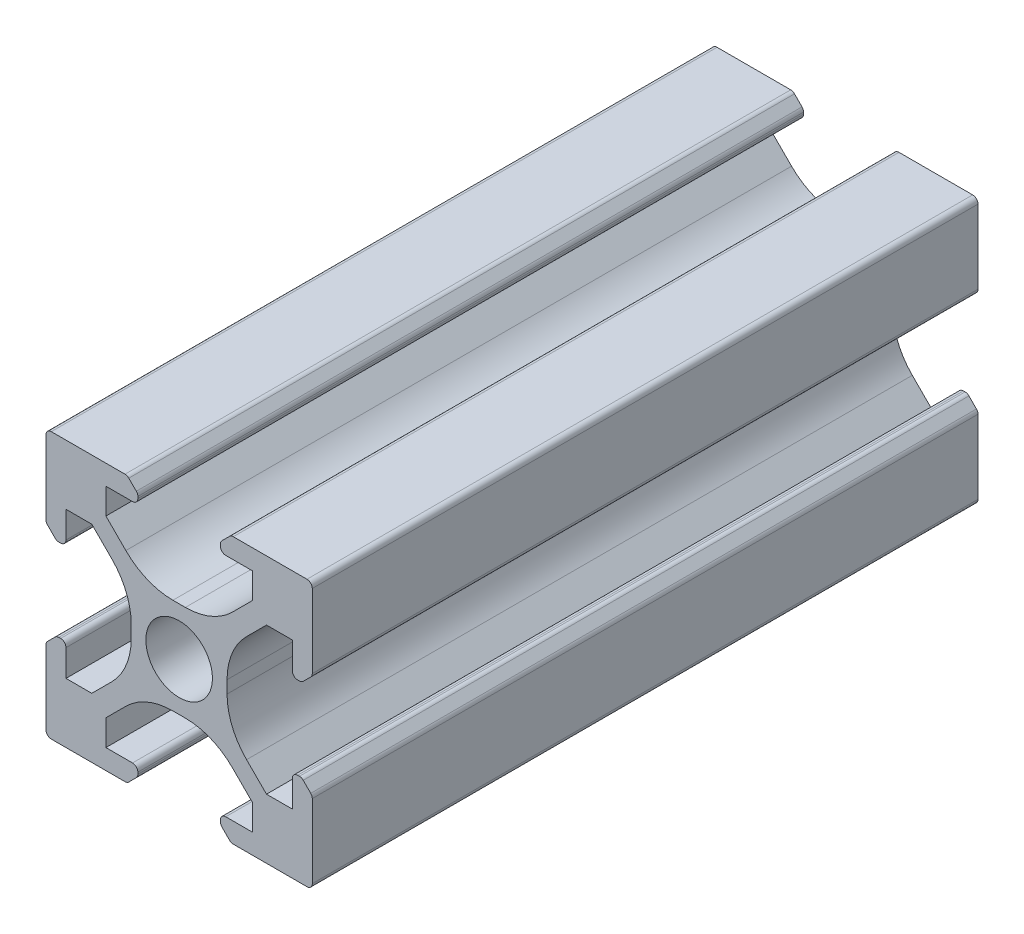
SolidWorks part; units mm, degrees
material "6063-T83"
ref_plane "Plano frontal" through (0, 0, 0) normal (0, 0, 1) x (1, 0, 0)
ref_plane "Plano superior" through (0, 0, 0) normal (0, 1, 0) x (1, 0, 0)
ref_plane "Plano direito" through (0, 0, 0) normal (1, 0, 0) x (0, 0, -1)
sketch "Esboço1" plane through (0, 0, 0) normal (0, 0, 1) x (1, 0, 0)
  line L0 (-9.0343, 3.1) -> (-8.9, 3.1)
  line L3 (-10, 10) -> (-4.0657, 10)
  line L5 (-10, -10) -> (10, 10) construction
  line L6 (-10, 10) -> (10, -10) construction
  line L7 (-8.5, 3.5) -> (-8.5, 5.5)
  line L8 (-10, 0) -> (10, 0) construction
  line L9 (0, 10) -> (0, -10) construction
  line L12 (-8.5, 5.5) -> (-6.5607, 5.5)
  line L15 (-6.5607, 5.5) -> (-5.0645, 4.0038)
  line L16 (-3.6, 0.4683) -> (-3.6, 0)
  line L17 (-0.4683, 3.6) -> (0, 3.6)
  line L18 (-5.5, 6.5607) -> (-4.0038, 5.0645)
  line L21 (-5.5, 8.5) -> (-5.5, 6.5607)
  line L24 (-3.5, 8.5) -> (-5.5, 8.5)
  line L25 (-3.1, 9.0343) -> (-3.1, 8.9)
  line L44 (-10, 4.0657) -> (-10, 10)
  line L45 (-9.8828, 3.7828) -> (-9.3172, 3.2172)
  line L46 (-3.7828, 9.8828) -> (-3.2172, 9.3172)
  line L47 (-3.6, 0) -> (-2.5, 0)
  line L48 (0, 3.6) -> (0, 2.5)
  arc A0 (-3.5, 8.5) -> (-3.1, 8.9) centre (-3.5, 8.9) ccw
  arc A1 (-3.7828, 9.8828) -> (-4.0657, 10) centre (-4.0657, 9.6) ccw
  arc A2 (-10, 4.0657) -> (-9.8828, 3.7828) centre (-9.6, 4.0657) ccw
  arc A3 (-8.5, 3.5) -> (-8.9, 3.1) centre (-8.9, 3.5) cw
  arc A4 (-3.2172, 9.3172) -> (-3.1, 9.0343) centre (-3.5, 9.0343) cw
  arc A5 (-9.3172, 3.2172) -> (-9.0343, 3.1) centre (-9.0343, 3.5) ccw
  arc A6 (-3.6, 0.4683) -> (-5.0645, 4.0038) centre (-8.6, 0.4683) ccw
  arc A7 (-4.0038, 5.0645) -> (-0.4683, 3.6) centre (-0.4683, 8.6) ccw
  circle A8 centre (0, 0) radius 2.5
  point P6 (-10, 3.1)
  point P28 (-3.1, 8.5)
  point P31 (-3.1, 10)
  point P33 (-3.9, 10)
  point P36 (-10, 3.9)
  point P39 (-8.5, 3.1)
  point P42 (-3.1, 9.2)
  point P45 (-9.2, 3.1)
  point P48 (-3.6, 2.5393)
  point P51 (-2.5393, 3.6)
  dimension "D5" = 10
  dimension "D9" = 0.4
  dimension "D10" = 0.4
  dimension "D11" = 5
  dimension "D12" = 5
  dimension "D13" = 5
  dimension "D1" = 6.9
  dimension "D2" = 1.5
  dimension "D3" = 3.6
  dimension "D4" = 1.5
  dimension "D6" = 2.4
  dimension "D7" = 3.6
  dimension "D8" = 45
extrude "Ressalto-extrusão1" add sketch "Esboço1" along normal blind 50
sketch "Esboço3" plane through (0, 0, 0) normal (1, 0, 0) x (0, 0, -1)
  line L0 (0, 0) -> (-1000, 0) construction
  dimension "D1" = 1000
pattern_circular "PadrãoCircular1" count 4 every 90 about axis through (0, 0, 0) along (0, 0, 1) of "Ressalto-extrusão1"
fillet "Filete1" radius 0.4 4 edges at (-10, -10, 25) (-10, 10, 25) (10, -10, 25) (10, 10, 25)
